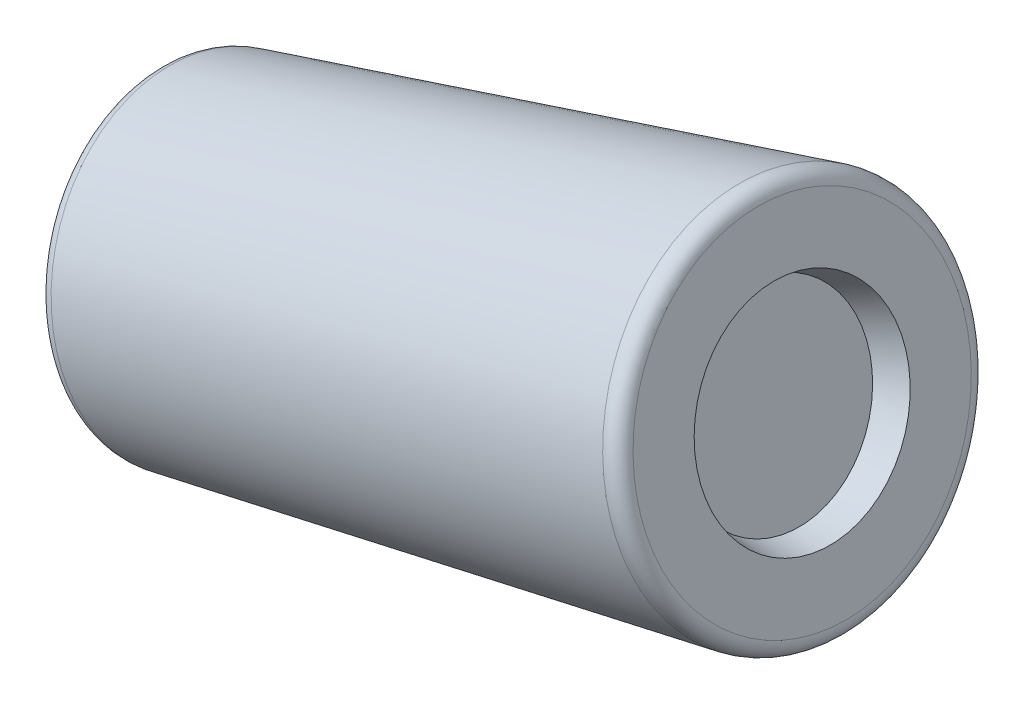
SolidWorks part; units mm, degrees
ref_plane "Plan1" through (0, 0, 0) normal (0, 0, 1) x (1, 0, 0)
ref_plane "Plan2" through (0, 0, 0) normal (0, 1, 0) x (1, 0, 0)
ref_plane "Plan3" through (0, 0, 0) normal (1, 0, 0) x (0, 0, -1)
sketch "Esquisse1" plane through (0, 0, 0) normal (0, 0, 1) x (1, 0, 0)
  line L0 (5.1368, 22.6555) -> (-76.4156, 0) construction
  line L1 (-3.671, 20.2087) -> (-13.7241, 17.4159)
  line L2 (0, 0) -> (-86.5472, 0) construction
  line L5 (-14, 16.4059) -> (-15, 16.1379) construction
  line L6 (-2.868, 17.3181) -> (-13.5693, 14.7983) construction
  line L7 (-2.868, 17.3181) -> (-13.132, 14.9013)
  line L8 (-2.868, 17.3181) -> (-3.671, 20.2087)
  line L9 (-13.7241, 17.4159) -> (-13.132, 14.9013)
  line L10 (-13.5693, 14.7983) -> (-14, 16.4059) construction
  line L11 (-76.4156, 0) -> (5.143, 19.2045) construction
  point P6 (-14, 16.4059)
  dimension "D2" = 0.5
  dimension "D3" = 3
revolve "Base-Révolution" add sketch "Esquisse1" angle 360 about L0
sketch "Esquisse3" plane through (1.8065, 0.4916, 0) normal (0.9635, 0.2677, 0) x (0, 0, -1)
  circle A0 centre (0, 20.4638) radius 1.75
  circle A2 centre (0, 20.4638) radius 3 construction
  dimension "D1" = 3.5
extrude "Enlèv. mat.-Extru.1" cut sketch "Esquisse3" against normal blind 0.5 draft 16
fillet "Congé1" radius 0.25
